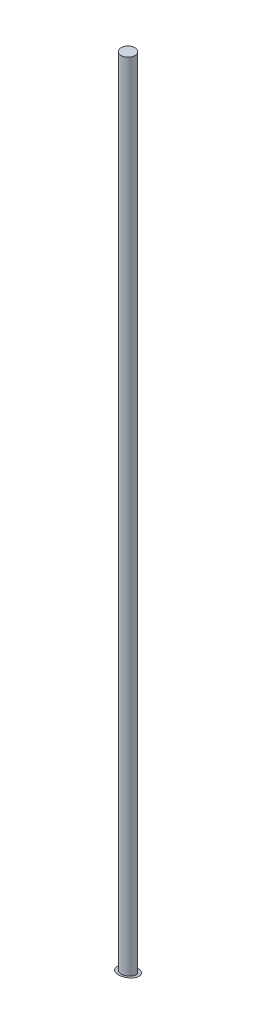
SolidWorks part; units mm, degrees
ref_plane "Спереди" through (0, 0, 0) normal (0, 0, 1) x (1, 0, 0)
ref_plane "Сверху" through (0, 0, 0) normal (0, 1, 0) x (1, 0, 0)
ref_plane "Справа" through (0, 0, 0) normal (1, 0, 0) x (0, 0, -1)
sketch "Эскиз1" plane through (0, 0, 0) normal (0, 1, 0) x (1, 0, 0)
  circle A0 centre (0, 0) radius 1.25
  dimension "D1" = 2.5
extrude "Бобышка-Вытянуть1" add sketch "Эскиз1" along normal blind 145
sketch "Эскиз3" plane through (0, 0, 0) normal (1, 0, 0) x (0, 0, -1)
  line L0 (1.25, 0) -> (-2.0806, 0.5999)
  line L1 (-1.25, 0) -> (1.25, 0) construction
  line L2 (-2.0806, 0.5999) -> (-2.0806, 0)
  line L3 (-2.0806, 0) -> (1.25, 0)
  dimension "D1" = 3.3842
  dimension "D2" = 10.21
extrude "Вырез-Вытянуть1" cut sketch "Эскиз3" against normal mid plane 12
sketch "Эскиз4" plane through (0, 0.2181, -0.0393) normal (0, -0.9842, 0.1773) x (1, 0, 0)
  circle A0 centre (0, 0.0404) radius 1.75
  dimension "D1" = 3.5
extrude "Бобышка-Вытянуть3" add sketch "Эскиз4" along normal blind 2 draft 64
